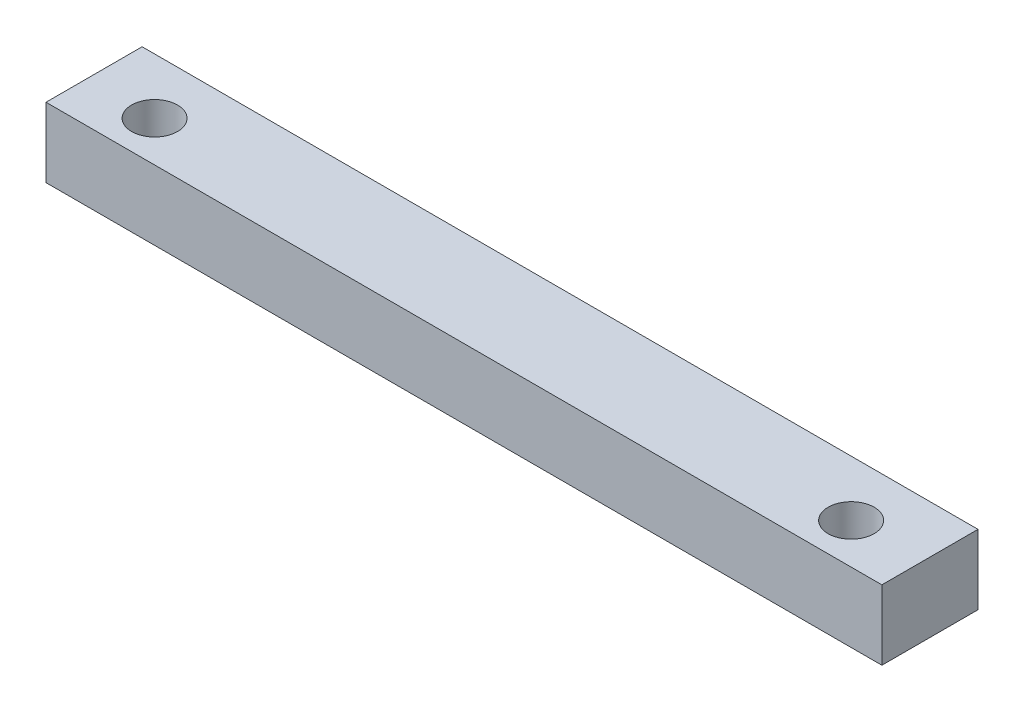
SolidWorks part; units mm, degrees
ref_plane "前视基准面" through (0, 0, 0) normal (0, 0, 1) x (1, 0, 0)
ref_plane "上视基准面" through (0, 0, 0) normal (0, 1, 0) x (1, 0, 0)
ref_plane "右视基准面" through (0, 0, 0) normal (1, 0, 0) x (0, 0, -1)
other "Configuration Table"
sketch "草图1" plane through (0, 0, 0) normal (0, 1, 0) x (1, 0, 0)
  line L1 (-42.9709, 4.5279) -> (17.0291, 4.5279)
  line L2 (-42.9709, 4.5279) -> (-42.9709, -2.3721)
  line L3 (-42.9709, -2.3721) -> (17.0291, -2.3721)
  line L4 (17.0291, 4.5279) -> (17.0291, -2.3721)
  dimension "D1" = 6.9
  dimension "D2" = 60
extrude "凸台-拉伸1" add sketch "草图1" along normal blind 5
sketch "草图2" plane through (0, 0, 0) normal (0, -1, 0) x (1, 0, 0)
  circle A0 centre (11.9231, -0.5279) radius 1.65
  circle A1 centre (-38.0769, -0.5279) radius 1.65
extrude "切除-拉伸1" cut sketch "草图2" against normal blind 10
